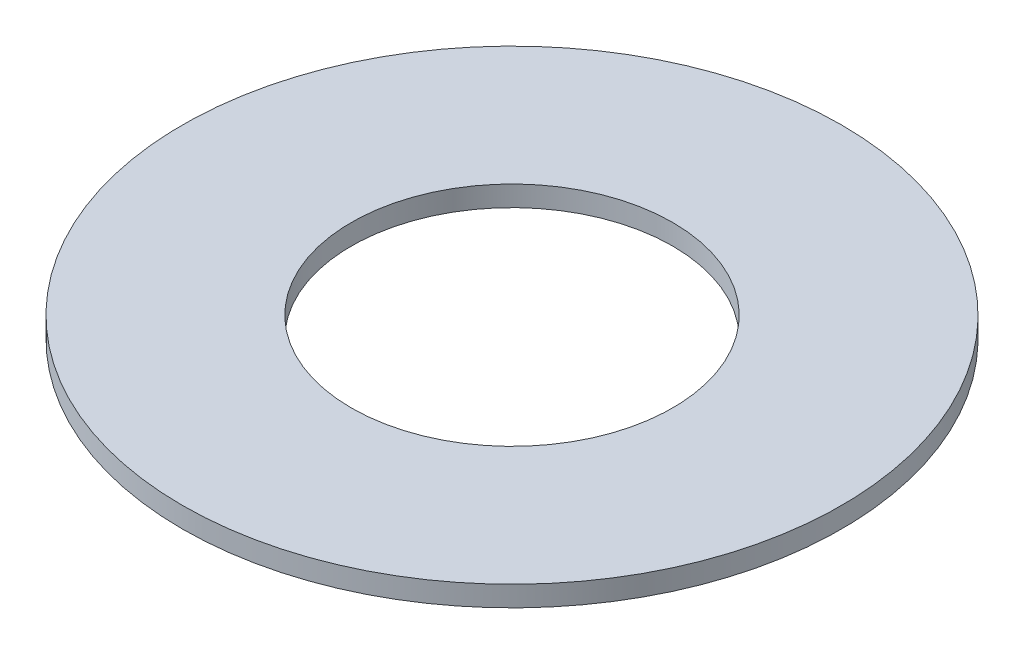
SolidWorks part; units mm, degrees
ref_plane "Front Plane" through (0, 0, 0) normal (0, 0, 1) x (1, 0, 0)
ref_plane "Top Plane" through (0, 0, 0) normal (0, 1, 0) x (1, 0, 0)
ref_plane "Right Plane" through (0, 0, 0) normal (1, 0, 0) x (0, 0, -1)
sketch "Sketch1" plane through (0, 0, 0) normal (0, 1, 0) x (1, 0, 0)
  circle A0 centre (0, 0) radius 15.7
  circle A1 centre (0, 0) radius 32.2
  dimension "D1" = 31.4
  dimension "D2" = 64.4
extrude "Boss-Extrude1" add sketch "Sketch1" along normal blind 2
